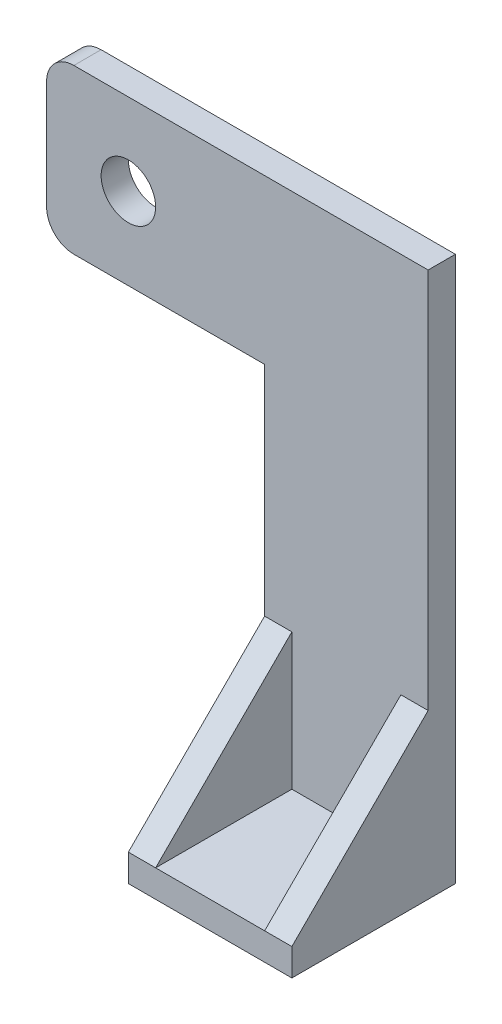
SolidWorks part; units mm, degrees
ref_plane "Front Plane" through (0, 0, 0) normal (0, 0, 1) x (1, 0, 0)
ref_plane "Top Plane" through (0, 0, 0) normal (0, 1, 0) x (1, 0, 0)
ref_plane "Right Plane" through (0, 0, 0) normal (1, 0, 0) x (0, 0, -1)
sketch "Sketch1" plane through (0, 0, 0) normal (0, 0, 1) x (1, 0, 0)
  line L0 (0, -15) -> (6.6093, -15) construction
  line L1 (5, 0) -> (70, 0)
  line L2 (0, -5) -> (0, -25)
  line L3 (5, -30) -> (40, -30)
  line L4 (70, 0) -> (70, -30)
  line L6 (70, -30) -> (70, -95)
  line L7 (70, -95) -> (40, -95)
  line L8 (40, -30) -> (40, -95)
  arc A1 (5, 0) -> (0, -5) centre (5, -5) ccw
  arc A2 (5, -30) -> (0, -25) centre (5, -25) cw
  dimension "D5" = 10
  dimension "D1" = 30
  dimension "D2" = 70
  dimension "D3" = 30
  dimension "D4" = 65
extrude "Boss-Extrude1" add sketch "Sketch1" along normal blind 5 contours L1 L4 L6 L7 L8 L3 A2 L2 A1
sketch "Sketch2" plane through (0, 0, 5) normal (0, 0, 1) x (1, 0, 0)
  line L0 (0, -5) -> (0, -25) construction
  line L1 (5, 0) -> (70, 0) construction
  circle A0 centre (15, -15) radius 5
  dimension "D1" = 10
  dimension "D2" = 15
  dimension "D3" = 15
extrude "Cut-Extrude1" cut sketch "Sketch2" against normal blind 10
sketch "Sketch3" plane through (0, -95, 0) normal (0, -1, 0) x (1, 0, 0)
  line L0 (70, 5) -> (70, 0) construction
  line L1 (40, 0) -> (70, 0)
  line L2 (40, 0) -> (40, 30)
  line L3 (40, 30) -> (70, 30)
  line L4 (70, 0) -> (70, 30)
  dimension "D1" = 30
extrude "Boss-Extrude2" add sketch "Sketch3" along normal blind 5
sketch "Sketch4" plane through (40, 0, 0) normal (-1, 0, 0) x (0, 0, 1)
  line L0 (5, -70) -> (30, -95)
  line L1 (5, -30) -> (5, -95) construction
  line L2 (30, -95) -> (5, -95)
  line L3 (5, -95) -> (5, -70)
extrude "Boss-Extrude3" add sketch "Sketch4" against normal blind 5
ref_plane "Plane1" through (55, 0, 0) normal (-1, 0, 0) x (0, 0, 1)
mirror "Mirror1" about plane through (55, 0, 0) normal (-1, 0, 0) of "Boss-Extrude3"
